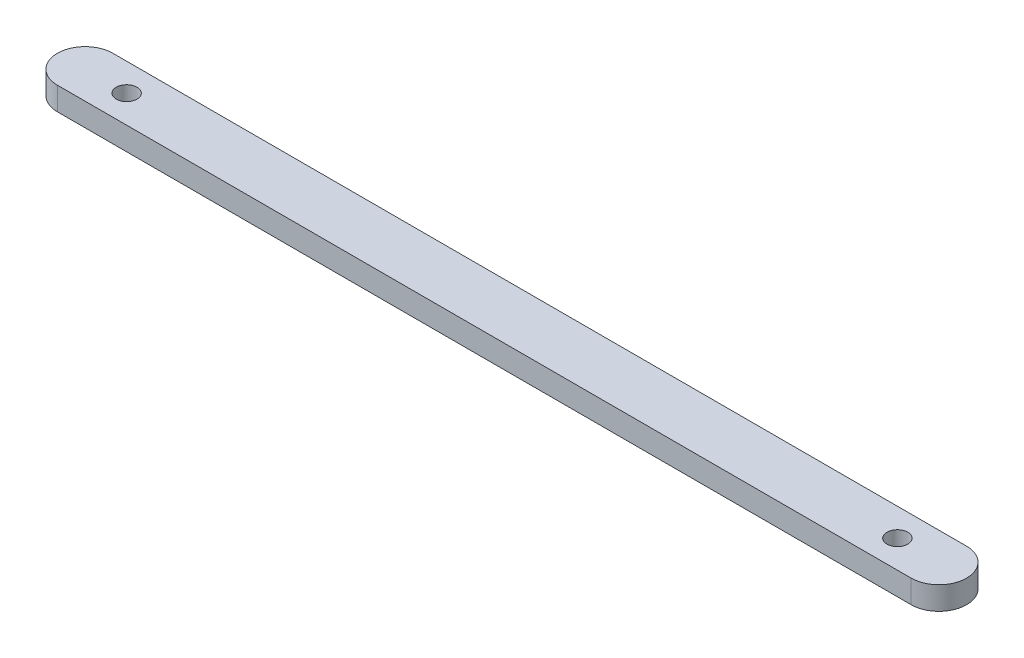
SolidWorks part; units mm, degrees
ref_plane "Front Plane" through (0, 0, 0) normal (0, 0, 1) x (1, 0, 0)
ref_plane "Top Plane" through (0, 0, 0) normal (0, 1, 0) x (1, 0, 0)
ref_plane "Right Plane" through (0, 0, 0) normal (1, 0, 0) x (0, 0, -1)
sketch "Sketch1" plane through (0, 0, 0) normal (0, 1, 0) x (1, 0, 0)
  line L0 (-40.3402, 0) -> (144.6598, 0) construction
  line L1 (-40.3402, 6) -> (144.6598, 6)
  line L2 (-40.3402, -6) -> (144.6598, -6)
  arc A0 (-40.3402, 6) -> (-40.3402, -6) centre (-40.3402, 0) ccw
  arc A1 (144.6598, -6) -> (144.6598, 6) centre (144.6598, 0) ccw
  point P3 (52.1598, 0)
  dimension "D1" = 12
  dimension "D2" = 185
extrude "Boss-Extrude1" add sketch "Sketch1" along normal blind 5
sketch "Sketch2" plane through (0, 5, 0) normal (0, 1, 0) x (1, 0, 0)
  line L0 (0, 0) -> (-113.0695, 0) construction
  line L1 (0, 1.4066) -> (0, 0) construction
  line L2 (0, 0) -> (179.7168, 0) construction
  line L3 (-46.3402, 0) -> (-46.3402, 22.0051) construction
  line L4 (150.6598, 0) -> (150.6598, 22.0051) construction
  circle A0 centre (-31.3402, 0) radius 2.25
  circle A1 centre (135.6598, 0) radius 2.25
  arc A2 (-40.3402, 6) -> (-40.3402, -6) centre (-40.3402, 0) ccw construction
  arc A3 (144.6598, -6) -> (144.6598, 6) centre (144.6598, 0) ccw construction
  point P19 (0, 0)
  point P20 (0, 0)
  point P21 (0, 0)
  dimension "D1" = 4.5
  dimension "D2" = 15
  dimension "D3" = 15
extrude "Cut-Extrude1" cut sketch "Sketch2" against normal blind 8
